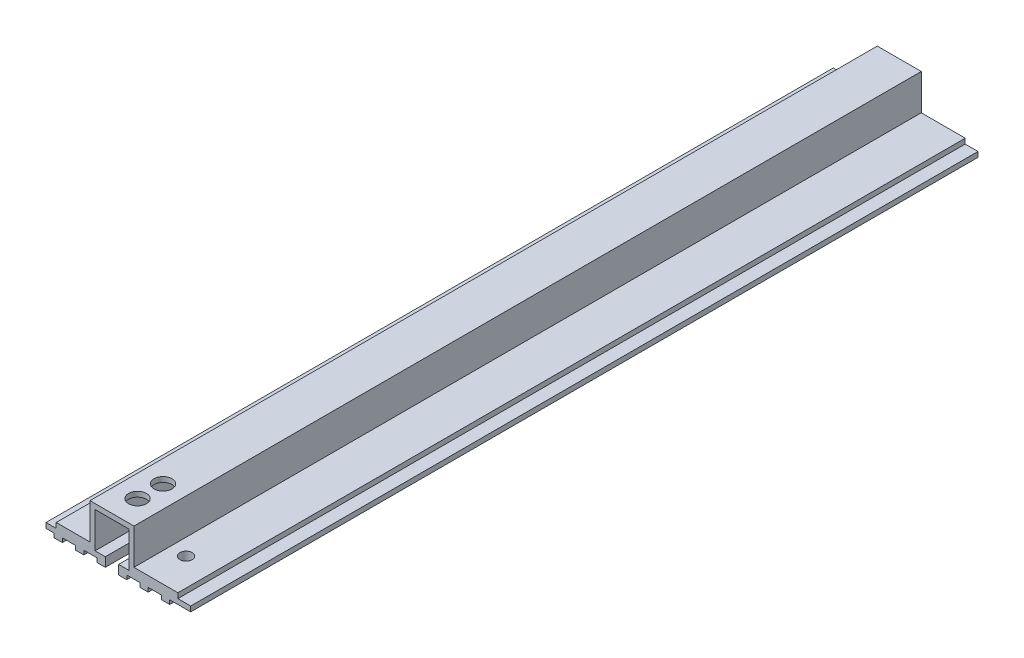
SolidWorks part; units mm, degrees
material "1023 Carbon Steel Sheet (SS)"
ref_plane "Front Plane" through (0, 0, 0) normal (0, 0, 1) x (1, 0, 0)
ref_plane "Top Plane" through (0, 0, 0) normal (0, 1, 0) x (1, 0, 0)
ref_plane "Right Plane" through (0, 0, 0) normal (1, 0, 0) x (0, 0, -1)
sketch "Sketch1" plane through (0, 0, 0) normal (0, 0, 1) x (1, 0, 0)
  line L0 (0, 0) -> (2.032, 0)
  line L1 (2.032, 0) -> (2.032, -1.016)
  line L2 (2.032, -1.016) -> (4.064, -1.016)
  line L3 (4.064, -1.016) -> (4.064, 0)
  line L4 (4.064, 0) -> (7.366, 0)
  line L5 (7.366, 0) -> (7.366, -1.016)
  line L6 (7.366, -1.016) -> (9.398, -1.016)
  line L7 (9.398, -1.016) -> (9.398, 0)
  line L8 (9.398, 0) -> (12.7, 0)
  line L9 (12.7, 0) -> (12.7, -1.016)
  line L10 (12.7, -1.016) -> (14.732, -1.016)
  line L11 (14.732, -1.016) -> (14.732, 0)
  line L12 (14.732, 0) -> (14.732, 1.27)
  line L13 (14.732, 1.27) -> (12.192, 1.27)
  line L14 (18.034, 0) -> (18.034, 1.27)
  line L15 (16.383, 30.9163) -> (16.383, -8.8632) construction
  line L16 (21.844, 11.43) -> (10.922, 11.43)
  line L17 (10.922, 11.43) -> (10.922, 2.54)
  line L18 (10.922, 2.54) -> (2.54, 2.54)
  line L19 (2.54, 2.54) -> (2.54, 1.27)
  line L20 (2.54, 1.27) -> (0, 1.27)
  line L21 (30.226, 2.54) -> (32.766, 2.54)
  line L22 (18.034, 1.27) -> (20.574, 1.27)
  line L23 (12.192, 1.27) -> (12.192, 10.16)
  line L24 (12.192, 10.16) -> (20.574, 10.16)
  line L25 (20.574, 1.27) -> (20.574, 10.16)
  line L26 (14.732, 1.27) -> (18.034, 1.27) construction
  line L27 (32.766, 2.54) -> (32.766, 1.27)
  line L28 (0, 0) -> (0, 1.27)
  line L30 (21.844, 2.54) -> (30.226, 2.54)
  line L31 (21.844, 11.43) -> (21.844, 2.54)
  line L34 (18.034, -1.016) -> (18.034, 0)
  line L35 (20.066, -1.016) -> (18.034, -1.016)
  line L36 (20.066, 0) -> (20.066, -1.016)
  line L37 (23.368, 0) -> (20.066, 0)
  line L38 (23.368, -1.016) -> (23.368, 0)
  line L39 (25.4, -1.016) -> (23.368, -1.016)
  line L40 (25.4, 0) -> (25.4, -1.016)
  line L41 (28.702, 0) -> (25.4, 0)
  line L42 (28.702, -1.016) -> (28.702, 0)
  line L43 (30.734, -1.016) -> (28.702, -1.016)
  line L44 (30.734, 0) -> (30.734, -1.016)
  line L45 (32.766, 0) -> (30.734, 0)
  line L49 (32.766, 1.27) -> (35.941, 1.27)
  line L51 (32.766, 0) -> (35.941, 0)
  line L52 (35.941, 1.27) -> (35.941, 0)
  point P27 (16.383, 10.16)
  point P35 (16.383, 11.43)
  dimension "D1" = 5.461
  dimension "D2" = 11.43
  dimension "D3" = 3.302
  dimension "D4" = 8.382
  dimension "D5" = 1.27
  dimension "D6" = 1.27
  dimension "D7" = 2.032
  dimension "D8" = 2.032
  dimension "D9" = 2.032
  dimension "D10" = 2.032
  dimension "D11" = 3.302
  dimension "D12" = 8.89
  dimension "D14" = 3.175
  dimension "D16" = 1.016
  dimension "D19" = 1.27
  dimension "D20" = 1.27
extrude "Boss-Extrude1" add sketch "Sketch1" against normal blind 195.58
sketch "Sketch2" plane through (0, 11.43, 0) normal (0, 1, 0) x (1, 0, 0)
  line L0 (21.844, 0) -> (10.922, 0) construction
  line L1 (16.383, 0) -> (16.383, 26.3536) construction
  circle A0 centre (16.383, 6.35) radius 2.2225
  circle A1 centre (16.383, 12.7) radius 2.2225
  dimension "D1" = 6.35
  dimension "D2" = 12.7
  dimension "D3" = 4.445
  dimension "D4" = 4.445
extrude "Cut-Extrude1" cut sketch "Sketch2" against normal up to next
sketch "Sketch5" plane through (0, 2.54, 0) normal (0, 1, 0) x (1, 0, 0)
  line L1 (32.766, 0) -> (21.844, 0) construction
  line L2 (32.766, 195.58) -> (32.766, 0) construction
  circle A0 centre (25.908, 8.89) radius 1.524
  dimension "D2" = 8.89
  dimension "D1" = 3.048
  dimension "D3" = 6.858
extrude "Cut-Extrude4" cut sketch "Sketch5" against normal through all
